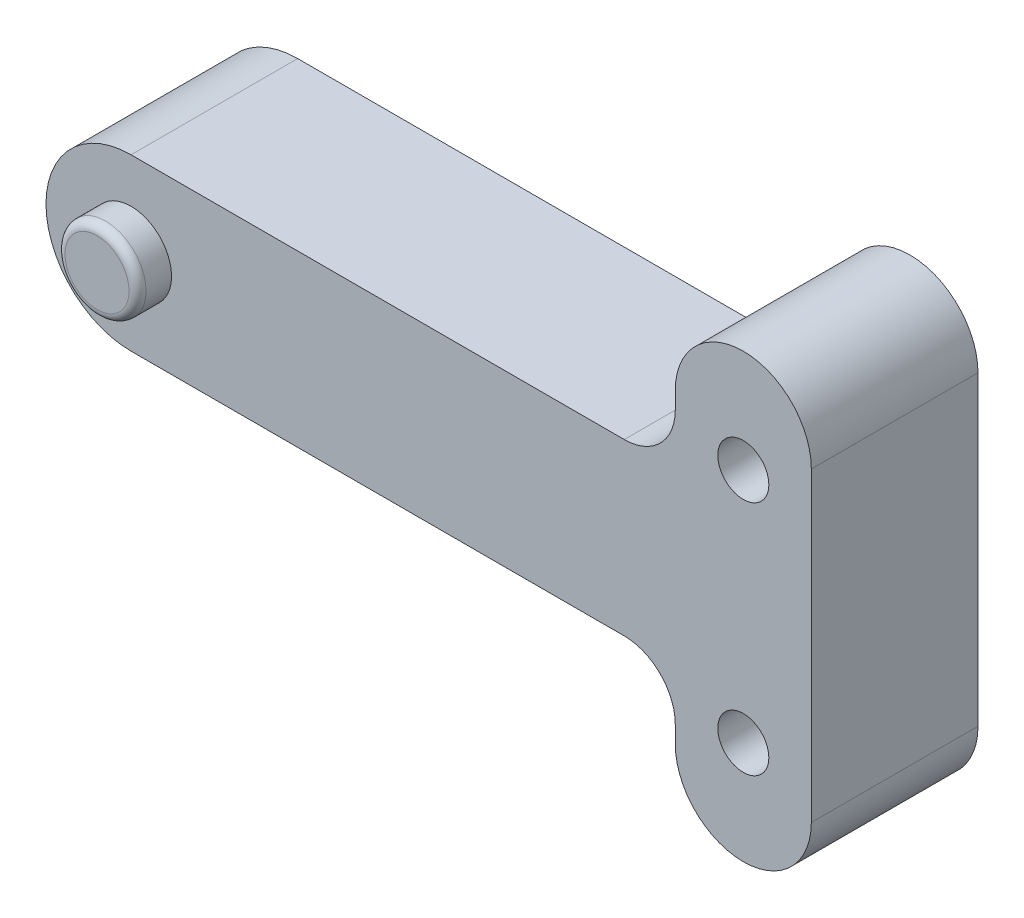
SolidWorks part; units mm, degrees
ref_plane "Front" through (0, 0, 0) normal (0, 0, 1) x (1, 0, 0)
ref_plane "Top" through (0, 0, 0) normal (0, 1, 0) x (1, 0, 0)
ref_plane "Right" through (0, 0, 0) normal (1, 0, 0) x (0, 0, -1)
sketch "Sketch1" plane through (0, 0, 0) normal (0, 0, 1) x (1, 0, 0)
  line L1 (-10, 10) -> (10, 10)
  line L2 (-10, 10) -> (-10, -10)
  line L3 (-10, -10) -> (10, -10)
  line L4 (10, 10) -> (10, -10)
  line L5 (-10, 10) -> (10, -10) construction
  line L6 (-10, -10) -> (10, 10) construction
  point P0 (0, 0)
  dimension "D1" = 20
  dimension "D2" = 20
extrude "Boss-Extrude1" add sketch "Sketch1" along normal mid plane 40
sketch "Sketch2" plane through (0, 0, 20) normal (0, 0, 1) x (1, 0, 0)
  line L0 (0, 5) -> (10, 5)
  line L1 (10, -10) -> (10, 10) construction
  line L2 (10, 5) -> (10, -5)
  line L3 (10, -5) -> (0, -5)
  arc A2 (0, 5) -> (0, -5) centre (0, 0) ccw
  line M6 (10, -10) -> (10, 10)
  line M7 (10, 10) -> (-10, 10)
  line M8 (-10, 10) -> (-10, -10)
  line M9 (-10, -10) -> (10, -10)
  dimension "D1" = 10
extrude "Cut-Extrude1" cut sketch "Sketch2" against normal through all both and the other way through all contours A2 L0 L3 M6 M7 M8 M9
sketch "Sketch3" plane through (0, 5, 0) normal (0, 1, 0) x (1, 0, 0)
  line L0 (-5, 20) -> (-5, -20) construction
  line L1 (-5, 4.9) -> (10, 4.9)
  line L3 (-5, -4.9) -> (10, -4.9)
  line L6 (-5, -4.9) -> (-5, -20)
  line L8 (10, -4.9) -> (10, -20)
  line L9 (10, 20) -> (-5, 20)
  line L10 (10, 20) -> (10, 4.9)
  line L11 (10, -20) -> (-5, -20)
  line L12 (-5, 20) -> (-5, 4.9)
  line L13 (-14.3, 0) -> (14.3, 0) construction
  dimension "D1" = 9.8
  dimension "D2" = 4.9
extrude "Cut-Extrude3" cut sketch "Sketch3" against normal through all both and the other way through all
sketch "Sketch5" plane through (0, 0, 0) normal (0, 0, 1) x (1, 0, 0)
  circle A0 centre (0, 0) radius 2.38
  dimension "D1" = 4.76
extrude "Boss-Extrude3" add sketch "Sketch5" along normal offset from surface 2 and the other way offset from surface (6.9 mm away) 2 up to face at (3.75, 0, 4.9) offset beyond the face yes other way up to face at (3.75, 0, -4.9)
fillet "Fillet1" radius 0.5 2 edges at (2.38, 0, -6.9) (-2.38, 0, 6.9)
sketch "Sketch7" plane through (10, 0, 0) normal (1, 0, 0) x (0, 0, -1)
  line L4 (-4.9, -5) -> (4.9, -5)
  line L5 (4.9, -5) -> (4.9, 5)
  line L6 (4.9, 5) -> (-4.9, 5)
  line L7 (-4.9, 5) -> (-4.9, -5)
  line L8 (-4.9, -5) -> (4.9, -5)
  line L9 (4.9, -5) -> (4.9, 5)
  line L10 (4.9, 5) -> (-4.9, 5)
  line L11 (-4.9, 5) -> (-4.9, -5)
  dimension "D1" = 0
extrude "Boss-Extrude4" add sketch "Sketch7" along normal blind 30
sketch "Sketch11" plane through (0, 0, 0) normal (0, 0, 1) x (1, 0, 0)
  line L2 (40, 5) -> (40, -5) construction
  line L4 (40, 9) -> (40, -9)
  line L6 (32, 9) -> (32, -9)
  line L7 (7.59, 0) -> (-7.59, 0) construction
  line L8 (0, 5) -> (40, 5) construction
  arc A1 (40, 9) -> (32, 9) centre (36, 9) ccw
  arc A2 (40, -9) -> (32, -9) centre (36, -9) cw
  point P9 (40, 0)
  dimension "D2" = 4
  dimension "D1" = 8
extrude "Boss-Extrude5" add sketch "Sketch11" along normal up to surface and the other way up to surface up to face at (-2.38, 0, 4.9) other way up to face at (2.38, 0, -4.9)
sketch "Sketch13" plane through (0, 0, 0) normal (0, 0, 1) x (1, 0, 0)
  line L1 (7.59, 0) -> (-7.59, 0) construction
  line L2 (36, 13) -> (36, -13) construction
  circle A4 centre (36, 6.95) radius 1.5
  circle A5 centre (36, -6.95) radius 1.5
  arc A6 (40, 9) -> (32, 9) centre (36, 9) ccw construction
  arc A7 (32, -9) -> (40, -9) centre (36, -9) ccw construction
  circle A8 centre (0, 0) radius 1.88 construction
  circle A9 centre (0, 0) radius 1.88
  dimension "D1" = 3
  dimension "D2" = 6.95
extrude "Cut-Extrude4" cut sketch "Sketch13" against normal through all both and the other way through all contours L2 A4 | A4 L2 | A5 L2 | L2 A5
fillet "Fillet2" radius 3 2 edges at (32, -5, 0) (32, 5, 0)
ref_plane "Plane1" through (0, 0, 0) normal (0, 0, 1) x (1, 0, 0)
